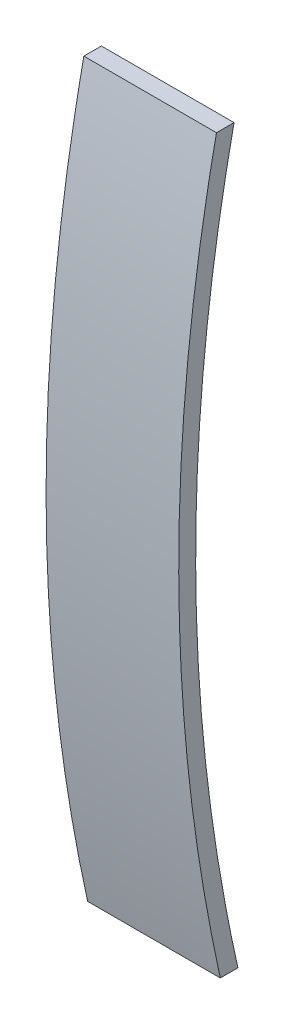
SolidWorks part; units mm, degrees
material "Glass"
ref_plane "Front Plane" through (0, 0, 0) normal (0, 0, 1) x (1, 0, 0)
ref_plane "Top Plane" through (0, 0, 0) normal (0, 1, 0) x (1, 0, 0)
ref_plane "Right Plane" through (0, 0, 0) normal (1, 0, 0) x (0, 0, -1)
sketch "Sketch2" plane through (0, 0, 0) normal (0, 0, 1) x (1, 0, 0)
  line L18 (0, 0) -> (381, 0)
  line L19 (0, 2108.2) -> (0, 0)
  line L20 (381, 0) -> (381, 2108.2)
  line L21 (381, 2108.2) -> (0, 2108.2)
  point P0 (0, 0)
extrude "Boss-Extrude1" add sketch "Sketch2" along normal mid plane 508
sketch "Sketch3" plane through (0, 0, 0) normal (-1, 0, 0) x (0, 0, 1)
  line L0 (61.5566, 2108.2) -> (254, 2108.2)
  line L1 (254, 2108.2) -> (254, 0)
  line L2 (254, 0) -> (50.5763, 0)
  line L3 (11.1504, 2108.2) -> (-254, 2108.2)
  line L4 (-254, 2108.2) -> (-254, 0)
  line L5 (-254, 0) -> (0, 0)
  line L6 (0, 0) -> (50.5763, 0)
  line L7 (61.5566, 2108.2) -> (11.1504, 2108.2)
  spline S6 degree 3 poles (50.5763, 0) (86.5281, 162.4154) (114.6064, 325.9112) (145.7247, 583.5786) (154.3426, 676.9847) (161.7634, 794.2023) (163.7383, 829.4021) (165.3338, 864.6539) (166.313, 888.1667) (166.7602, 899.927) (168.7831, 958.7128) (169.7205, 1005.7235) (170.4948, 1146.7019) (168.2936, 1240.616) (160.9345, 1381.3803) (157.0229, 1440.0098) (152.057, 1498.6116) (149.9864, 1522.0501) (148.9088, 1533.77) (145.5513, 1568.9082) (143.1467, 1592.3074) (122.385, 1781.1439) (95.9194, 1945.2972) (61.5566, 2108.2) knots 0.028847 0.028847 0.028847 0.028847 0.25 0.25 0.375 0.375 0.40625 0.421875 0.421875 0.4375 0.4375 0.5 0.5 0.625 0.625 0.6875 0.703125 0.703125 0.71875 0.71875 0.75 0.75 0.971226 0.971226 0.971226 0.971226
  spline S7 degree 3 poles (11.1504, 2108.2) (46.0305, 1945.3722) (72.9368, 1781.1422) (92.741, 1603.7291) (94.0057, 1592.016) (96.4493, 1568.5899) (99.9867, 1533.4456) (107.3436, 1451.4065) (112.1088, 1381.0257) (119.5776, 1240.182) (121.808, 1146.1766) (121.1356, 1028.5317) (120.6744, 993.2279) (119.8231, 957.9085) (119.1689, 934.3588) (118.7985, 922.5869) (116.7317, 863.7647) (114.3898, 816.8042) (105.3241, 676.2108) (96.5606, 582.866) (64.9477, 325.4413) (36.4507, 162.1591) (0, 0) knots 0.028788 0.028788 0.028788 0.028788 0.25 0.25 0.265625 0.265625 0.28125 0.3125 0.375 0.375 0.5 0.5 0.53125 0.546875 0.546875 0.5625 0.5625 0.625 0.625 0.75 0.75 0.971112 0.971112 0.971112 0.971112
extrude "Cut-Extrude1" cut sketch "Sketch3" against normal through all contours L3 S7 L5 L4 | L2 S6 L0 L1
ref_plane "Plane1" through (-2.54, 0, 0) normal (-1, 0, 0) x (0, 0, 1)
ref_plane "Plane2" through (383.54, 0, 0) normal (1, 0, 0) x (0, 0, -1)
ref_plane "Plane3" through (0, 2110.74, 0) normal (0, 1, 0) x (1, 0, 0)
ref_plane "Plane4" through (0, 0, 0) normal (0, -0.0053, 1) x (1, 0, 0)
